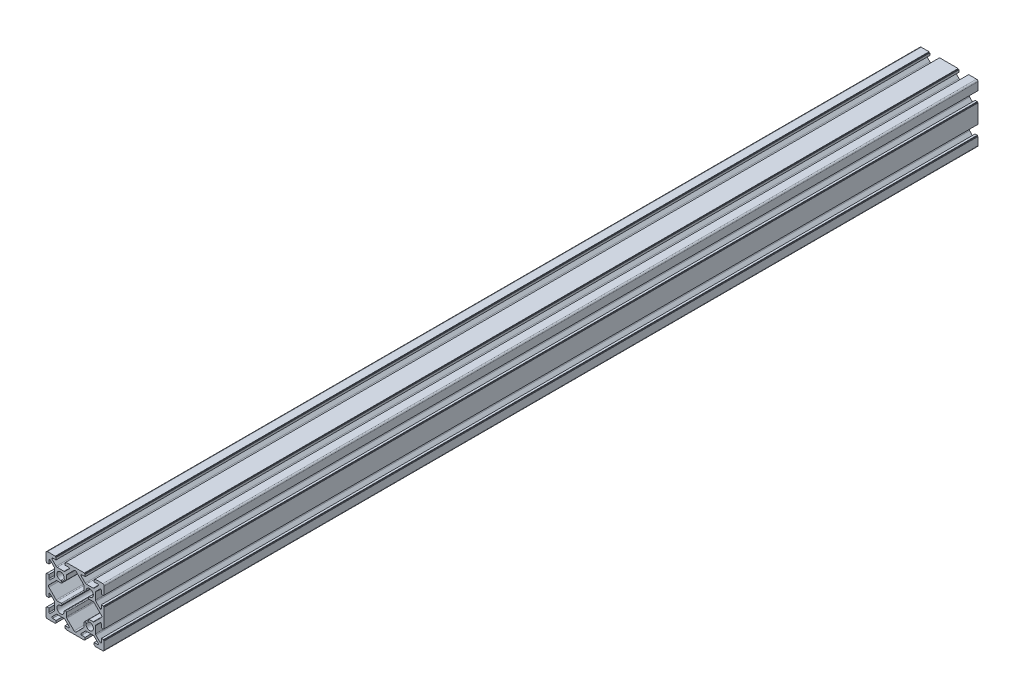
SolidWorks part; units mm, degrees
ref_plane "前视基准面" through (0, 0, 0) normal (0, 0, 1) x (1, 0, 0)
ref_plane "上视基准面" through (0, 0, 0) normal (0, 1, 0) x (1, 0, 0)
ref_plane "右视基准面" through (0, 0, 0) normal (1, 0, 0) x (0, 0, -1)
sketch "草图1" plane through (0, 0, 0) normal (0, 0, 1) x (1, 0, 0)
  line L0 (31.4283, 33.0307) -> (31.2907, 33.5441)
  line L1 (28.8233, 31.0766) -> (29.3366, 30.9391)
  line L2 (28.1939, 27.8605) -> (28.1939, 30.5937)
  line L3 (22.901, 22.1534) -> (27.901, 27.1534)
  line L4 (16.4868, 27.1534) -> (21.4868, 22.1534)
  line L5 (16.1939, 30.5937) -> (16.1939, 27.8605)
  line L6 (15.0511, 30.9391) -> (15.5645, 31.0766)
  line L7 (13.097, 33.5441) -> (12.9595, 33.0307)
  line L8 (9.8809, 34.1735) -> (12.6141, 34.1735)
  line L9 (4.1738, 39.4664) -> (9.1738, 34.4664)
  line L10 (9.1738, 45.8806) -> (4.1738, 40.8806)
  line L11 (12.6141, 46.1735) -> (9.8809, 46.1735)
  line L12 (12.9595, 47.3162) -> (13.097, 46.8029)
  line L13 (15.5645, 49.2703) -> (15.0511, 49.4079)
  line L14 (16.1939, 52.4865) -> (16.1939, 49.7533)
  line L15 (21.4868, 58.1936) -> (16.4868, 53.1936)
  line L16 (27.901, 53.1936) -> (22.901, 58.1936)
  line L17 (28.1939, 49.7533) -> (28.1939, 52.4865)
  line L18 (29.3366, 49.4079) -> (28.8233, 49.2703)
  line L19 (31.2907, 46.8029) -> (31.4283, 47.3162)
  line L20 (34.5069, 46.1735) -> (31.7737, 46.1735)
  line L21 (40.214, 40.8806) -> (35.214, 45.8806)
  line L22 (35.214, 34.4664) -> (40.214, 39.4664)
  line L23 (31.7737, 34.1735) -> (34.5069, 34.1735)
  line L24 (29.1738, 25.8806) -> (26.3202, 23.027)
  line L25 (34.5069, 26.1735) -> (29.8809, 26.1735)
  line L26 (38.0675, 23.027) -> (35.214, 25.8806)
  line L27 (35.2939, 22.1735) -> (37.714, 22.1735)
  line L28 (35.2939, 20.6735) -> (35.2939, 22.1735)
  line L29 (35.7939, 20.6735) -> (35.2939, 20.6735)
  line L30 (35.7939, 20.1735) -> (35.7939, 20.6735)
  line L31 (41.1939, 20.1735) -> (35.7939, 20.1735)
  line L32 (42.1939, 26.5735) -> (42.1939, 21.1735)
  line L33 (41.6939, 26.5735) -> (42.1939, 26.5735)
  line L34 (41.6939, 27.0735) -> (41.6939, 26.5735)
  line L35 (40.1939, 27.0735) -> (41.6939, 27.0735)
  line L36 (40.1939, 24.6534) -> (40.1939, 27.0735)
  line L37 (36.4868, 27.1534) -> (39.3403, 24.2998)
  line L38 (36.1939, 32.4865) -> (36.1939, 27.8605)
  line L39 (39.3403, 36.0471) -> (36.4868, 33.1936)
  line L40 (40.1939, 33.2735) -> (40.1939, 35.6936)
  line L41 (41.6939, 33.2735) -> (40.1939, 33.2735)
  line L42 (41.6939, 33.7735) -> (41.6939, 33.2735)
  line L43 (42.1939, 33.7735) -> (41.6939, 33.7735)
  line L44 (42.1939, 46.5735) -> (42.1939, 33.7735)
  line L45 (41.6939, 46.5735) -> (42.1939, 46.5735)
  line L46 (41.6939, 47.0735) -> (41.6939, 46.5735)
  line L47 (40.1939, 47.0735) -> (41.6939, 47.0735)
  line L48 (40.1939, 44.6534) -> (40.1939, 47.0735)
  line L49 (36.4868, 47.1534) -> (39.3403, 44.2998)
  line L50 (36.1939, 52.4865) -> (36.1939, 47.8605)
  line L51 (39.3403, 56.0471) -> (36.4868, 53.1936)
  line L52 (40.1939, 53.2735) -> (40.1939, 55.6936)
  line L53 (41.6939, 53.2735) -> (40.1939, 53.2735)
  line L54 (41.6939, 53.7735) -> (41.6939, 53.2735)
  line L55 (42.1939, 53.7735) -> (41.6939, 53.7735)
  line L56 (42.1939, 59.1735) -> (42.1939, 53.7735)
  line L57 (35.7939, 60.1735) -> (41.1939, 60.1735)
  line L58 (35.7939, 59.6735) -> (35.7939, 60.1735)
  line L59 (35.2939, 59.6735) -> (35.7939, 59.6735)
  line L60 (35.2939, 58.1735) -> (35.2939, 59.6735)
  line L61 (37.714, 58.1735) -> (35.2939, 58.1735)
  line L62 (35.214, 54.4664) -> (38.0675, 57.3199)
  line L63 (29.8809, 54.1735) -> (34.5069, 54.1735)
  line L64 (26.3202, 57.3199) -> (29.1738, 54.4664)
  line L65 (29.0939, 58.1735) -> (26.6738, 58.1735)
  line L66 (29.0939, 59.6735) -> (29.0939, 58.1735)
  line L67 (28.5939, 59.6735) -> (29.0939, 59.6735)
  line L68 (28.5939, 60.1735) -> (28.5939, 59.6735)
  line L69 (15.7939, 60.1735) -> (28.5939, 60.1735)
  line L70 (15.7939, 59.6735) -> (15.7939, 60.1735)
  line L71 (15.2939, 59.6735) -> (15.7939, 59.6735)
  line L72 (15.2939, 58.1735) -> (15.2939, 59.6735)
  line L73 (17.714, 58.1735) -> (15.2939, 58.1735)
  line L74 (15.214, 54.4664) -> (18.0675, 57.3199)
  line L75 (9.8809, 54.1735) -> (14.5069, 54.1735)
  line L76 (6.3202, 57.3199) -> (9.1738, 54.4664)
  line L77 (9.0939, 58.1735) -> (6.6738, 58.1735)
  line L78 (9.0939, 59.6735) -> (9.0939, 58.1735)
  line L79 (8.5939, 59.6735) -> (9.0939, 59.6735)
  line L80 (8.5939, 60.1735) -> (8.5939, 59.6735)
  line L81 (3.1939, 60.1735) -> (8.5939, 60.1735)
  line L82 (2.1939, 53.7735) -> (2.1939, 59.1735)
  line L83 (2.6939, 53.7735) -> (2.1939, 53.7735)
  line L84 (2.6939, 53.2735) -> (2.6939, 53.7735)
  line L85 (4.1939, 53.2735) -> (2.6939, 53.2735)
  line L86 (4.1939, 55.6936) -> (4.1939, 53.2735)
  line L87 (7.901, 53.1936) -> (5.0474, 56.0471)
  line L88 (8.1939, 47.8605) -> (8.1939, 52.4865)
  line L89 (5.0474, 44.2998) -> (7.901, 47.1534)
  line L90 (4.1939, 47.0735) -> (4.1939, 44.6534)
  line L91 (2.6939, 47.0735) -> (4.1939, 47.0735)
  line L92 (2.6939, 46.5735) -> (2.6939, 47.0735)
  line L93 (2.1939, 46.5735) -> (2.6939, 46.5735)
  line L94 (2.1939, 33.7735) -> (2.1939, 46.5735)
  line L95 (2.6939, 33.7735) -> (2.1939, 33.7735)
  line L96 (2.6939, 33.2735) -> (2.6939, 33.7735)
  line L97 (4.1939, 33.2735) -> (2.6939, 33.2735)
  line L98 (4.1939, 35.6936) -> (4.1939, 33.2735)
  line L99 (7.901, 33.1936) -> (5.0474, 36.0471)
  line L100 (8.1939, 27.8605) -> (8.1939, 32.4865)
  line L101 (5.0474, 24.2998) -> (7.901, 27.1534)
  line L102 (4.1939, 27.0735) -> (4.1939, 24.6534)
  line L103 (2.6939, 27.0735) -> (4.1939, 27.0735)
  line L104 (2.6939, 26.5735) -> (2.6939, 27.0735)
  line L105 (2.1939, 26.5735) -> (2.6939, 26.5735)
  line L106 (2.1939, 21.1735) -> (2.1939, 26.5735)
  line L107 (8.5939, 20.1735) -> (3.1939, 20.1735)
  line L108 (8.5939, 20.6735) -> (8.5939, 20.1735)
  line L109 (9.0939, 20.6735) -> (8.5939, 20.6735)
  line L110 (9.0939, 22.1735) -> (9.0939, 20.6735)
  line L111 (6.6738, 22.1735) -> (9.0939, 22.1735)
  line L112 (9.1738, 25.8806) -> (6.3202, 23.027)
  line L113 (14.5069, 26.1735) -> (9.8809, 26.1735)
  line L114 (18.0675, 23.027) -> (15.214, 25.8806)
  line L115 (15.2939, 22.1735) -> (17.714, 22.1735)
  line L116 (15.2939, 20.6735) -> (15.2939, 22.1735)
  line L117 (15.7939, 20.6735) -> (15.2939, 20.6735)
  line L118 (15.7939, 20.1735) -> (15.7939, 20.6735)
  line L119 (28.5939, 20.1735) -> (15.7939, 20.1735)
  line L120 (28.5939, 20.6735) -> (28.5939, 20.1735)
  line L121 (29.0939, 20.6735) -> (28.5939, 20.6735)
  line L122 (29.0939, 22.1735) -> (29.0939, 20.6735)
  line L123 (26.6738, 22.1735) -> (29.0939, 22.1735)
  arc A0 (31.4283, 33.0307) -> (31.9584, 32.6623) centre (31.9112, 33.1601) ccw
  arc A1 (29.705, 30.409) -> (31.9584, 32.6623) centre (32.1939, 30.1735) ccw
  arc A2 (29.705, 30.409) -> (29.3366, 30.9391) centre (29.2072, 30.4561) ccw
  arc A3 (28.8233, 31.0766) -> (28.1939, 30.5937) centre (28.6939, 30.5937) ccw
  arc A4 (27.901, 27.1534) -> (28.1939, 27.8605) centre (27.1939, 27.8605) ccw
  arc A5 (21.4868, 22.1534) -> (22.901, 22.1534) centre (22.1939, 22.8605) ccw
  arc A6 (16.1939, 27.8605) -> (16.4868, 27.1534) centre (17.1939, 27.8605) ccw
  arc A7 (16.1939, 30.5937) -> (15.5645, 31.0766) centre (15.6939, 30.5937) ccw
  arc A8 (15.0511, 30.9391) -> (14.6828, 30.409) centre (15.1805, 30.4561) ccw
  arc A9 (12.4294, 32.6623) -> (14.6828, 30.409) centre (12.1939, 30.1735) ccw
  arc A10 (12.4294, 32.6623) -> (12.9595, 33.0307) centre (12.4765, 33.1601) ccw
  arc A11 (13.097, 33.5441) -> (12.6141, 34.1735) centre (12.6141, 33.6735) ccw
  arc A12 (9.1738, 34.4664) -> (9.8809, 34.1735) centre (9.8809, 35.1735) ccw
  arc A13 (4.1738, 40.8806) -> (4.1738, 39.4664) centre (4.8809, 40.1735) ccw
  arc A14 (9.8809, 46.1735) -> (9.1738, 45.8806) centre (9.8809, 45.1735) ccw
  arc A15 (12.6141, 46.1735) -> (13.097, 46.8029) centre (12.6141, 46.6735) ccw
  arc A16 (12.9595, 47.3162) -> (12.4294, 47.6846) centre (12.4765, 47.1868) ccw
  arc A17 (14.6828, 49.9379) -> (12.4294, 47.6846) centre (12.1939, 50.1735) ccw
  arc A18 (14.6828, 49.9379) -> (15.0511, 49.4079) centre (15.1805, 49.8908) ccw
  arc A19 (15.5645, 49.2703) -> (16.1939, 49.7533) centre (15.6939, 49.7533) ccw
  arc A20 (16.4868, 53.1936) -> (16.1939, 52.4865) centre (17.1939, 52.4865) ccw
  arc A21 (22.901, 58.1936) -> (21.4868, 58.1936) centre (22.1939, 57.4865) ccw
  arc A22 (28.1939, 52.4865) -> (27.901, 53.1936) centre (27.1939, 52.4865) ccw
  arc A23 (28.1939, 49.7533) -> (28.8233, 49.2703) centre (28.6939, 49.7533) ccw
  arc A24 (29.3366, 49.4079) -> (29.705, 49.9379) centre (29.2072, 49.8908) ccw
  arc A25 (31.9584, 47.6846) -> (29.705, 49.9379) centre (32.1939, 50.1735) ccw
  arc A26 (31.9584, 47.6846) -> (31.4283, 47.3162) centre (31.9112, 47.1868) ccw
  arc A27 (31.2907, 46.8029) -> (31.7737, 46.1735) centre (31.7737, 46.6735) ccw
  arc A28 (35.214, 45.8806) -> (34.5069, 46.1735) centre (34.5069, 45.1735) ccw
  arc A29 (40.214, 39.4664) -> (40.214, 40.8806) centre (39.5069, 40.1735) ccw
  arc A30 (34.5069, 34.1735) -> (35.214, 34.4664) centre (34.5069, 35.1735) ccw
  arc A31 (31.7737, 34.1735) -> (31.2907, 33.5441) centre (31.7737, 33.6735) ccw
  arc A32 (26.3202, 23.027) -> (26.6738, 22.1735) centre (26.6738, 22.6735) ccw
  arc A33 (29.8809, 26.1735) -> (29.1738, 25.8806) centre (29.8809, 25.1735) ccw
  arc A34 (35.214, 25.8806) -> (34.5069, 26.1735) centre (34.5069, 25.1735) ccw
  arc A35 (37.714, 22.1735) -> (38.0675, 23.027) centre (37.714, 22.6735) ccw
  arc A36 (41.1939, 20.1735) -> (42.1939, 21.1735) centre (41.1939, 21.1735) ccw
  arc A37 (39.3403, 24.2998) -> (40.1939, 24.6534) centre (39.6939, 24.6534) ccw
  arc A38 (36.1939, 27.8605) -> (36.4868, 27.1534) centre (37.1939, 27.8605) ccw
  arc A39 (36.4868, 33.1936) -> (36.1939, 32.4865) centre (37.1939, 32.4865) ccw
  arc A40 (40.1939, 35.6936) -> (39.3403, 36.0471) centre (39.6939, 35.6936) ccw
  arc A41 (39.3403, 44.2998) -> (40.1939, 44.6534) centre (39.6939, 44.6534) ccw
  arc A42 (36.1939, 47.8605) -> (36.4868, 47.1534) centre (37.1939, 47.8605) ccw
  arc A43 (36.4868, 53.1936) -> (36.1939, 52.4865) centre (37.1939, 52.4865) ccw
  arc A44 (40.1939, 55.6936) -> (39.3403, 56.0471) centre (39.6939, 55.6936) ccw
  arc A45 (42.1939, 59.1735) -> (41.1939, 60.1735) centre (41.1939, 59.1735) ccw
  arc A46 (38.0675, 57.3199) -> (37.714, 58.1735) centre (37.714, 57.6735) ccw
  arc A47 (34.5069, 54.1735) -> (35.214, 54.4664) centre (34.5069, 55.1735) ccw
  arc A48 (29.1738, 54.4664) -> (29.8809, 54.1735) centre (29.8809, 55.1735) ccw
  arc A49 (26.6738, 58.1735) -> (26.3202, 57.3199) centre (26.6738, 57.6735) ccw
  arc A50 (18.0675, 57.3199) -> (17.714, 58.1735) centre (17.714, 57.6735) ccw
  arc A51 (14.5069, 54.1735) -> (15.214, 54.4664) centre (14.5069, 55.1735) ccw
  arc A52 (9.1738, 54.4664) -> (9.8809, 54.1735) centre (9.8809, 55.1735) ccw
  arc A53 (6.6738, 58.1735) -> (6.3202, 57.3199) centre (6.6738, 57.6735) ccw
  arc A54 (3.1939, 60.1735) -> (2.1939, 59.1735) centre (3.1939, 59.1735) ccw
  arc A55 (5.0474, 56.0471) -> (4.1939, 55.6936) centre (4.6939, 55.6936) ccw
  arc A56 (8.1939, 52.4865) -> (7.901, 53.1936) centre (7.1939, 52.4865) ccw
  arc A57 (7.901, 47.1534) -> (8.1939, 47.8605) centre (7.1939, 47.8605) ccw
  arc A58 (4.1939, 44.6534) -> (5.0474, 44.2998) centre (4.6939, 44.6534) ccw
  arc A59 (5.0474, 36.0471) -> (4.1939, 35.6936) centre (4.6939, 35.6936) ccw
  arc A60 (8.1939, 32.4865) -> (7.901, 33.1936) centre (7.1939, 32.4865) ccw
  arc A61 (7.901, 27.1534) -> (8.1939, 27.8605) centre (7.1939, 27.8605) ccw
  arc A62 (4.1939, 24.6534) -> (5.0474, 24.2998) centre (4.6939, 24.6534) ccw
  arc A63 (2.1939, 21.1735) -> (3.1939, 20.1735) centre (3.1939, 21.1735) ccw
  arc A64 (6.3202, 23.027) -> (6.6738, 22.1735) centre (6.6738, 22.6735) ccw
  arc A65 (9.8809, 26.1735) -> (9.1738, 25.8806) centre (9.8809, 25.1735) ccw
  arc A66 (15.214, 25.8806) -> (14.5069, 26.1735) centre (14.5069, 25.1735) ccw
  arc A67 (17.714, 22.1735) -> (18.0675, 23.027) centre (17.714, 22.6735) ccw
extrude "拉伸1" add sketch "草图1" along normal blind 600
